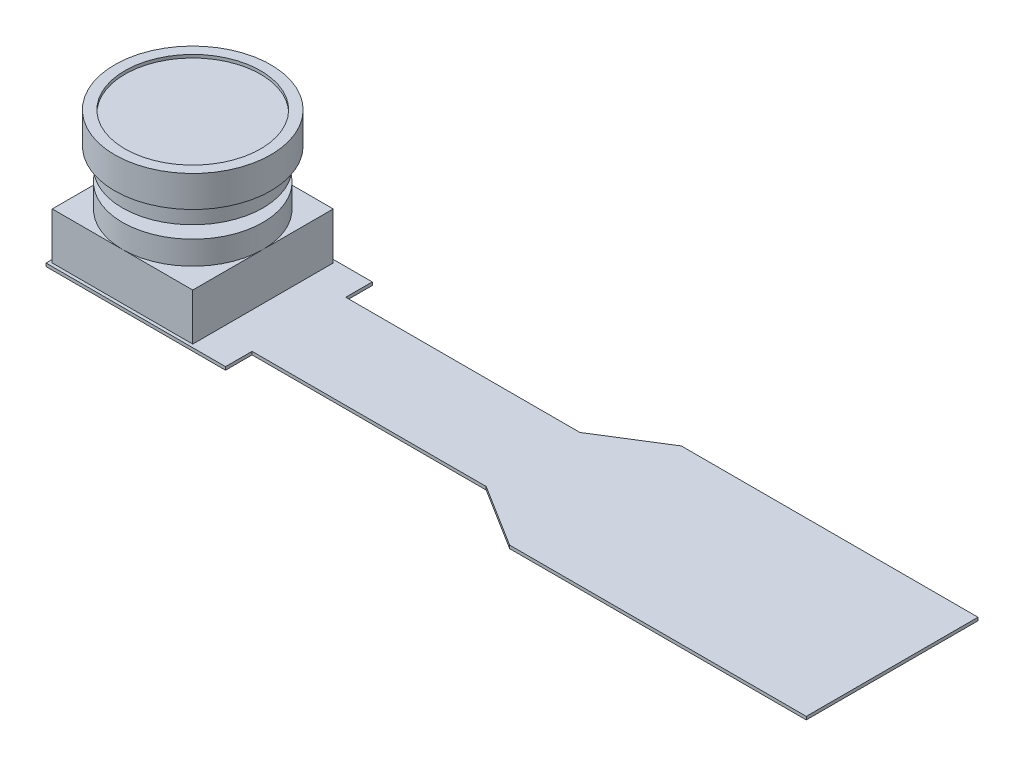
SolidWorks part; units mm, degrees
ref_plane "Front Plane" through (0, 0, 0) normal (0, 0, 1) x (1, 0, 0)
ref_plane "Top Plane" through (0, 0, 0) normal (0, 1, 0) x (1, 0, 0)
ref_plane "Right Plane" through (0, 0, 0) normal (1, 0, 0) x (0, 0, -1)
sketch "Sketch1" plane through (0, 0, 0) normal (0, 1, 0) x (1, 0, 0)
  line L1 (4.5, -4.5) -> (-4.5, -4.5)
  line L2 (4.5, -4.5) -> (4.5, 4.5)
  line L3 (4.5, 4.5) -> (-4.5, 4.5)
  line L4 (-4.5, -4.5) -> (-4.5, 4.5)
  line L5 (4.5, -4.5) -> (-4.5, 4.5) construction
  line L6 (4.5, 4.5) -> (-4.5, -4.5) construction
  point P0 (0, 0)
  dimension "D1" = 9
extrude "Boss-Extrude1" add sketch "Sketch1" along normal blind 3
sketch "Sketch2" plane through (0, 3, 0) normal (0, 1, 0) x (1, 0, 0)
  circle A0 centre (0, 0) radius 4.5
extrude "Boss-Extrude2" add sketch "Sketch2" along normal blind 1.5
sketch "Sketch3" plane through (0, 4.5, 0) normal (0, 1, 0) x (1, 0, 0)
  circle A0 centre (0, 0) radius 3.25
  dimension "D1" = 6.5
extrude "Boss-Extrude3" add sketch "Sketch3" along normal blind 0.8
sketch "Sketch4" plane through (0, 5.3, 0) normal (0, 1, 0) x (1, 0, 0)
  circle A0 centre (0, 0) radius 4.5 construction
  circle A1 centre (0, 0) radius 4.5
extrude "Boss-Extrude4" add sketch "Sketch4" along normal blind 1.2
sketch "Sketch6" plane through (0, 6.5, 0) normal (0, 1, 0) x (1, 0, 0)
  circle A0 centre (0, 0) radius 5
  dimension "D1" = 10
extrude "Boss-Extrude5" add sketch "Sketch6" along normal blind 2
sketch "Sketch7" plane through (0, 8.5, 0) normal (0, 1, 0) x (1, 0, 0)
  circle A0 centre (0, 0) radius 4.3449
extrude "Cut-Extrude1" cut sketch "Sketch7" against normal blind 0.2
sketch "Sketch8" plane through (0, 0, 0) normal (0, -1, 0) x (1, 0, 0)
  line L0 (6.8, 4.7) -> (6.8, 3)
  line L1 (-4.7, 4.7) -> (6.8, 4.7)
  line L2 (-4.7, 4.7) -> (-4.7, -4.7)
  line L3 (-4.7, -4.7) -> (6.8, -4.7)
  line L5 (6.8, 3) -> (21.8, 3)
  line L7 (6.8, -3) -> (21.8, -3)
  line L9 (25.8, 5.5) -> (44.8, 5.5)
  line L11 (25.8, -5.5) -> (44.8, -5.5)
  line L12 (44.8, 5.5) -> (44.8, -5.5)
  line L13 (6.8, 3) -> (6.8, -3) construction
  line L14 (6.8, -4.7) -> (6.8, -3)
  line L15 (-4.5, 4.5) -> (4.5, 4.5) construction
  line L16 (-4.5, -4.5) -> (-4.5, 4.5) construction
  line L17 (4.5, -4.5) -> (-4.5, -4.5) construction
  line L18 (0, 0) -> (6.8, 0) construction
  line L19 (21.8, 3) -> (25.8, 5.5)
  line L20 (21.8, -3) -> (25.8, -5.5)
  line L21 (25.8, -5.5) -> (25.8, 5.5) construction
  line L22 (21.8, 3) -> (21.8, -3) construction
  line L23 (21.8, 0) -> (25.8, 0) construction
  dimension "D1" = 0.2
  dimension "D2" = 0.2
  dimension "D3" = 0.2
  dimension "D4" = 11.5
  dimension "D5" = 6
  dimension "D6" = 4
  dimension "D7" = 11
  dimension "D8" = 15
  dimension "D9" = 19
extrude "Boss-Extrude6" add sketch "Sketch8" along normal blind 0.2
